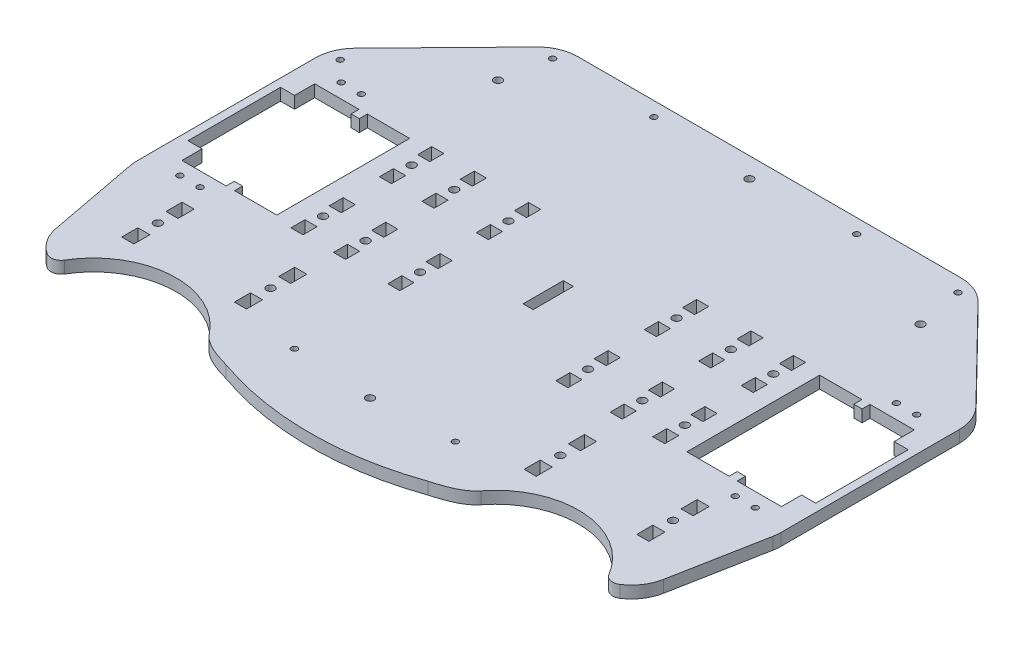
SolidWorks part; units mm, degrees
material "Balsa"
ref_plane "Plan de face" through (0, 0, 0) normal (0, 0, 1) x (1, 0, 0)
ref_plane "Plan de dessus" through (0, 0, 0) normal (0, 1, 0) x (1, 0, 0)
ref_plane "Plan de droite" through (0, 0, 0) normal (1, 0, 0) x (0, 0, -1)
sketch "Esquisse1" plane through (0, 0, 0) normal (0, 1, 0) x (1, 0, 0)
  line L0 (-159.6514, 61.9965) -> (-151.003, 16.2822)
  line L1 (131.3515, 0) -> (50.1768, 0)
  line L2 (0, 0) -> (0, 220) construction
  line L3 (95.3188, 220) -> (-95.3188, 220)
  line L4 (-160, 65.7142) -> (-160, 154.2858)
  line L5 (-154.3028, 168.2654) -> (-109.6216, 213.9796)
  line L6 (0, 110) -> (-160, 110) construction
  line L7 (154.3028, 168.2654) -> (109.6216, 213.9796)
  line L8 (160, 65.7142) -> (160, 154.2858)
  line L9 (159.6514, 61.9965) -> (151.003, 16.2822)
  line L10 (-50.1768, 0) -> (-131.3515, 0)
  arc A0 (-151.003, 16.2822) -> (-131.3515, 0) centre (-131.3515, 20) ccw
  arc A1 (-159.6514, 61.9965) -> (-160, 65.7142) centre (-140, 65.7142) cw
  arc A2 (-109.6216, 213.9796) -> (-95.3188, 220) centre (-95.3188, 200) cw
  arc A3 (-154.3028, 168.2654) -> (-160, 154.2858) centre (-140, 154.2858) ccw
  arc A4 (154.3028, 168.2654) -> (160, 154.2858) centre (140, 154.2858) cw
  arc A5 (109.6216, 213.9796) -> (95.3188, 220) centre (95.3188, 200) ccw
  arc A6 (159.6514, 61.9965) -> (160, 65.7142) centre (140, 65.7142) ccw
  arc A7 (151.003, 16.2822) -> (131.3515, 0) centre (131.3515, 20) cw
  arc A8 (-50.1768, 0) -> (50.1768, 0) centre (0, 142.6245) ccw
  dimension "D3" = 20
  dimension "D1" = 220
  dimension "D2" = 160
extrude "Boss.-Extru.1" add sketch "Esquisse1" along normal blind 6
sketch "Esquisse2" plane through (0, 6, 0) normal (0, 1, 0) x (1, 0, 0)
  line L0 (0, 220) -> (0, 0) construction
  line L1 (95.3188, 220) -> (-95.3188, 220) construction
  line L2 (0, -16) -> (-100, -16) construction
  line L3 (0, -16) -> (0, 0) construction
  line L4 (50.1768, 0) -> (131.3515, 0) construction
  line L5 (-50.1768, 0) -> (-59.2136, -20.1799)
  line L6 (50.1768, 0) -> (59.2136, -20.1799)
  arc A0 (-67.535, 9.0405) -> (-59.2136, -20.1799) centre (-100, -16) ccw
  arc A1 (-50.1768, 0) -> (50.1768, 0) centre (0, 142.6245) ccw construction
  arc A2 (67.535, 9.0405) -> (59.2136, -20.1799) centre (100, -16) cw
  spline S0 degree 3 poles (-50.1768, 0) (-51.8745, 0.5973) (-62.853, 2.9703) (-67.535, 9.0405) knots 0 0 0 0 1 1 1 1
  spline S1 degree 3 poles (50.1768, 0) (51.8745, 0.5973) (62.853, 2.9703) (67.535, 9.0405) knots 0 0 0 0 1 1 1 1
  dimension "D2" = 82
  dimension "D1" = 16
extrude "Enlèv. mat.-Extru.1" cut sketch "Esquisse2" against normal blind 6
fillet "Congé1" radius 5 2 edges at (-137.3461, 3, -0.9195) (137.3461, 3, -0.9195)
sketch "Esquisse3" plane through (0, 6, 0) normal (0, 1, 0) x (-1, 0, 0)
  line L0 (160, -110) -> (0, -110) construction
  line L1 (160, -154.2858) -> (160, -65.7142) construction
  line L2 (0, -110) -> (0, 8.569) construction
  line L3 (89.9, -119) -> (89.9, -101) construction
  line L4 (92.9, -145) -> (86.9, -145)
  line L5 (92.9, -145) -> (92.9, -138)
  line L6 (92.9, -138) -> (86.9, -138)
  line L7 (86.9, -145) -> (86.9, -138)
  line L8 (92.9, -126) -> (86.9, -126)
  line L9 (92.9, -126) -> (92.9, -119)
  line L10 (92.9, -119) -> (86.9, -119)
  line L11 (86.9, -126) -> (86.9, -119)
  line L12 (92.9, -101) -> (86.9, -101)
  line L13 (92.9, -101) -> (92.9, -94)
  line L14 (92.9, -94) -> (86.9, -94)
  line L15 (86.9, -101) -> (86.9, -94)
  line L16 (92.9, -82) -> (86.9, -82)
  line L17 (92.9, -82) -> (92.9, -75)
  line L18 (92.9, -75) -> (86.9, -75)
  line L19 (86.9, -82) -> (86.9, -75)
  line L20 (71.76, -145) -> (65.76, -145)
  line L21 (2.5, -120) -> (-2.5, -120)
  line L22 (2.5, -120) -> (2.5, -100)
  line L23 (2.5, -100) -> (-2.5, -100)
  line L24 (-2.5, -120) -> (-2.5, -100)
  line L25 (71.76, -145) -> (71.76, -138)
  line L26 (71.76, -138) -> (65.76, -138)
  line L27 (65.76, -145) -> (65.76, -138)
  line L28 (71.76, -126) -> (65.76, -126)
  line L29 (71.76, -126) -> (71.76, -119)
  line L30 (71.76, -119) -> (65.76, -119)
  line L31 (65.76, -126) -> (65.76, -119)
  line L32 (71.76, -101) -> (65.76, -101)
  line L33 (71.76, -101) -> (71.76, -94)
  line L34 (71.76, -94) -> (65.76, -94)
  line L35 (65.76, -101) -> (65.76, -94)
  line L36 (71.76, -82) -> (65.76, -82)
  line L37 (71.76, -82) -> (71.76, -75)
  line L38 (71.76, -75) -> (65.76, -75)
  line L39 (65.76, -82) -> (65.76, -75)
  line L40 (68.76, -119) -> (68.76, -101) construction
  line L41 (44.76, -145) -> (38.76, -145)
  line L42 (44.76, -145) -> (44.76, -138)
  line L43 (44.76, -138) -> (38.76, -138)
  line L44 (38.76, -145) -> (38.76, -138)
  line L45 (44.76, -126) -> (38.76, -126)
  line L46 (44.76, -126) -> (44.76, -119)
  line L47 (44.76, -119) -> (38.76, -119)
  line L48 (38.76, -126) -> (38.76, -119)
  line L49 (44.76, -101) -> (38.76, -101)
  line L50 (44.76, -101) -> (44.76, -94)
  line L51 (44.76, -94) -> (38.76, -94)
  line L52 (38.76, -101) -> (38.76, -94)
  line L53 (44.76, -82) -> (38.76, -82)
  line L54 (44.76, -82) -> (44.76, -75)
  line L55 (44.76, -75) -> (38.76, -75)
  line L56 (38.76, -82) -> (38.76, -75)
  line L57 (41.76, -119) -> (41.76, -101) construction
  line L58 (89.9, -138) -> (89.9, -126) construction
  line L59 (89.9, -94) -> (89.9, -82) construction
  line L60 (-38.76, -82) -> (-38.76, -75)
  line L61 (-44.76, -75) -> (-38.76, -75)
  line L62 (-44.76, -82) -> (-44.76, -75)
  line L63 (-44.76, -82) -> (-38.76, -82)
  line L64 (-38.76, -101) -> (-38.76, -94)
  line L65 (-44.76, -94) -> (-38.76, -94)
  line L66 (-44.76, -101) -> (-44.76, -94)
  line L67 (-44.76, -101) -> (-38.76, -101)
  line L68 (-65.76, -82) -> (-65.76, -75)
  line L69 (-71.76, -75) -> (-65.76, -75)
  line L70 (-71.76, -82) -> (-71.76, -75)
  line L71 (-71.76, -82) -> (-65.76, -82)
  line L72 (-65.76, -101) -> (-65.76, -94)
  line L73 (-71.76, -94) -> (-65.76, -94)
  line L74 (-71.76, -101) -> (-71.76, -94)
  line L75 (-71.76, -101) -> (-65.76, -101)
  line L76 (-86.9, -82) -> (-86.9, -75)
  line L77 (-92.9, -75) -> (-86.9, -75)
  line L78 (-92.9, -82) -> (-92.9, -75)
  line L79 (-92.9, -82) -> (-86.9, -82)
  line L80 (-86.9, -101) -> (-86.9, -94)
  line L81 (-92.9, -94) -> (-86.9, -94)
  line L82 (-92.9, -101) -> (-92.9, -94)
  line L83 (-92.9, -101) -> (-86.9, -101)
  line L84 (-38.76, -126) -> (-38.76, -119)
  line L85 (-44.76, -119) -> (-38.76, -119)
  line L86 (-44.76, -126) -> (-44.76, -119)
  line L87 (-44.76, -126) -> (-38.76, -126)
  line L88 (-65.76, -126) -> (-65.76, -119)
  line L89 (-71.76, -119) -> (-65.76, -119)
  line L90 (-71.76, -126) -> (-71.76, -119)
  line L91 (-71.76, -126) -> (-65.76, -126)
  line L92 (-86.9, -126) -> (-86.9, -119)
  line L93 (-92.9, -119) -> (-86.9, -119)
  line L94 (-92.9, -126) -> (-92.9, -119)
  line L95 (-92.9, -126) -> (-86.9, -126)
  line L96 (-38.76, -145) -> (-38.76, -138)
  line L97 (-44.76, -138) -> (-38.76, -138)
  line L98 (-44.76, -145) -> (-44.76, -138)
  line L99 (-44.76, -145) -> (-38.76, -145)
  line L100 (-65.76, -145) -> (-65.76, -138)
  line L101 (-71.76, -138) -> (-65.76, -138)
  line L102 (-71.76, -145) -> (-71.76, -138)
  line L103 (-71.76, -145) -> (-65.76, -145)
  line L104 (-86.9, -145) -> (-86.9, -138)
  line L105 (-92.9, -138) -> (-86.9, -138)
  line L106 (-92.9, -145) -> (-92.9, -138)
  line L107 (-92.9, -145) -> (-86.9, -145)
  line L108 (0, -110) -> (-139.191, -110) construction
  line L109 (101.9, -143) -> (122.9, -143)
  line L110 (101.9, -143) -> (101.9, -77)
  line L111 (101.9, -77) -> (122.9, -77)
  line L112 (122.9, -143) -> (122.9, -77)
  line L114 (-101.9, -143) -> (-122.9, -143)
  line L115 (-101.9, -143) -> (-101.9, -77)
  line L116 (-101.9, -77) -> (-122.9, -77)
  line L117 (-122.9, -143) -> (-122.9, -77)
  arc A0 (50.1768, 0) -> (-50.1768, 0) centre (0, -142.6245) ccw construction
  circle A1 centre (89.9, -132) radius 2
  circle A2 centre (89.9, -88) radius 2
  circle A3 centre (68.76, -88) radius 2
  circle A4 centre (68.76, -132) radius 2
  circle A5 centre (41.76, -132) radius 2
  circle A6 centre (41.76, -88) radius 2
  circle A7 centre (-41.76, -88) radius 2
  circle A8 centre (-68.76, -88) radius 2
  circle A9 centre (-89.9, -88) radius 2
  circle A10 centre (-41.76, -132) radius 2
  circle A11 centre (-68.76, -132) radius 2
  circle A12 centre (-89.9, -132) radius 2
  point P26 (89.9, -110)
  point P51 (68.76, -110)
  point P69 (41.76, -110)
  point P149 (122.9, -110)
  point P155 (-101.9, -110)
  dimension "D16" = 4
  dimension "D17" = 4
  dimension "D1" = 70
  dimension "D2" = 12
  dimension "D3" = 7
  dimension "D4" = 7
  dimension "D5" = 12
  dimension "D6" = 7
  dimension "D7" = 7
  dimension "D8" = 86.9
  dimension "D9" = 6
  dimension "D10" = 2.5
  dimension "D11" = 2.5
  dimension "D12" = 20
  dimension "D13" = 10
  dimension "D20" = 9
  dimension "D21" = 21
  dimension "D22" = 66
  dimension "D23" = 66
  dimension "D24" = 9
  dimension "D25" = 21
  dimension "D14" = 2
  dimension "D15" = 2
  dimension "D18" = 2
  dimension "D19" = 2
extrude "Enlèv. mat.-Extru.2" cut sketch "Esquisse3" against normal blind 6
sketch "Esquisse4" plane through (0, 6, 0) normal (0, 1, 0) x (1, 0, 0)
  line L0 (-160, 154.2858) -> (-160, 65.7142) construction
  line L1 (-131, 59) -> (-125, 59)
  line L2 (-131, 59) -> (-131, 51)
  line L3 (-131, 51) -> (-125, 51)
  line L4 (-125, 59) -> (-125, 51)
  line L5 (-122.9, 77) -> (-101.9, 77) construction
  line L6 (-100, 25) -> (-100, 54.6944) construction
  line L7 (-131, 37) -> (-125, 37)
  line L8 (-131, 37) -> (-131, 29)
  line L9 (-131, 29) -> (-125, 29)
  line L10 (-125, 37) -> (-125, 29)
  line L11 (-75, 37) -> (-75, 29)
  line L12 (-69, 29) -> (-75, 29)
  line L13 (-69, 37) -> (-69, 29)
  line L14 (-69, 37) -> (-75, 37)
  line L15 (-75, 59) -> (-75, 51)
  line L16 (-69, 51) -> (-75, 51)
  line L17 (-69, 59) -> (-69, 51)
  line L18 (-69, 59) -> (-75, 59)
  line L19 (0, -8.569) -> (0, 51) construction
  line L20 (69, 59) -> (75, 59)
  line L21 (69, 59) -> (69, 51)
  line L22 (69, 51) -> (75, 51)
  line L23 (75, 59) -> (75, 51)
  line L24 (69, 37) -> (75, 37)
  line L25 (69, 37) -> (69, 29)
  line L26 (69, 29) -> (75, 29)
  line L27 (75, 37) -> (75, 29)
  line L28 (125, 37) -> (125, 29)
  line L29 (131, 29) -> (125, 29)
  line L30 (131, 37) -> (131, 29)
  line L31 (131, 37) -> (125, 37)
  line L32 (125, 59) -> (125, 51)
  line L33 (131, 51) -> (125, 51)
  line L34 (131, 59) -> (131, 51)
  line L35 (131, 59) -> (125, 59)
  arc A0 (-67.535, 9.0405) -> (-135.2708, 4.9039) centre (-100, -16) ccw construction
  arc A1 (-50.1768, 0) -> (50.1768, 0) centre (0, 142.6245) ccw construction
  dimension "D1" = 29
  dimension "D2" = 6
  dimension "D3" = 8
  dimension "D4" = 18
  dimension "D5" = 30
  dimension "D6" = 8
extrude "Enlèv. mat.-Extru.3" cut sketch "Esquisse4" against normal blind 10
sketch "Esquisse5" plane through (0, 6, 0) normal (0, 1, 0) x (1, 0, 0)
  line L0 (-133.0593, 190) -> (133.0593, 190) construction
  line L1 (-109.6216, 213.9796) -> (-154.3028, 168.2654) construction
  line L2 (154.3028, 168.2654) -> (109.6216, 213.9796) construction
  line L3 (95.3188, 220) -> (-95.3188, 220) construction
  line L4 (0, 220) -> (0, 190) construction
  circle A0 centre (-105, 190) radius 2
  circle A1 centre (105, 190) radius 2
  dimension "D2" = 4
  dimension "D1" = 30
  dimension "D3" = 105
extrude "Enlèv. mat.-Extru.4" cut sketch "Esquisse5" against normal blind 10
sketch "Esquisse6" plane through (0, 6, 0) normal (0, 1, 0) x (1, 0, 0)
  line L0 (0, 220) -> (0, 164.9198) construction
  line L1 (95.3188, 220) -> (-95.3188, 220) construction
  circle A0 centre (0, 210) radius 2
  dimension "D1" = 4
  dimension "D2" = 10
extrude "Enlèv. mat.-Extru.5" cut sketch "Esquisse6" against normal blind 10
sketch "Esquisse7" plane through (0, 6, 0) normal (0, 1, 0) x (-1, 0, 0)
  line L0 (0, 8.569) -> (0, -35.6546) construction
  arc A0 (50.1768, 0) -> (-50.1768, 0) centre (0, -142.6245) ccw construction
  circle A1 centre (0, -21.431) radius 2
  dimension "D2" = 4
  dimension "D1" = 30
extrude "Enlèv. mat.-Extru.6" cut sketch "Esquisse7" against normal blind 10
sketch "Esquisse9" plane through (0, 6, 0) normal (0, 1, 0) x (-1, 0, 0)
  line L0 (128, -51) -> (128, -37) construction
  line L1 (131, -51) -> (125, -51) construction
  line L2 (125, -37) -> (131, -37) construction
  line L3 (72, -51) -> (72, -37) construction
  line L4 (75, -51) -> (69, -51) construction
  line L5 (69, -37) -> (75, -37) construction
  line L6 (-72, -51) -> (-72, -37) construction
  line L7 (-69, -51) -> (-75, -51) construction
  line L8 (-75, -37) -> (-69, -37) construction
  line L9 (-128, -51) -> (-128, -37) construction
  line L10 (-125, -51) -> (-131, -51) construction
  line L11 (-131, -37) -> (-125, -37) construction
  circle A0 centre (128, -44) radius 2
  circle A1 centre (72, -44) radius 2
  circle A2 centre (-72, -44) radius 2
  circle A3 centre (-128, -44) radius 2
  dimension "D1" = 4
  dimension "D2" = 4
  dimension "D3" = 4
  dimension "D4" = 4
extrude "Enlèv. mat.-Extru.8" cut sketch "Esquisse9" against normal blind 10
sketch "Esquisse8" plane through (0, 6, 0) normal (0, 1, 0) x (1, 0, 0)
  line L0 (122.9, 77) -> (122.9, 143) construction
  line L1 (-127, 142.9255) -> (-149, 142.9255)
  line L2 (-127, 142.9255) -> (-127, 139)
  line L3 (-127, 76.9255) -> (-149, 76.9255)
  line L4 (-156, 132.9255) -> (-156, 86.9255)
  line L5 (0, 220) -> (0, -8.569) construction
  line L6 (95.3188, 220) -> (-95.3188, 220) construction
  line L7 (-122.9, 110) -> (-101.9, 110) construction
  line L8 (-101.9, 77) -> (-101.9, 143) construction
  line L9 (-160, 154.2858) -> (-160, 65.7142) construction
  line L10 (127, 81) -> (127, 76.9255)
  line L11 (122.9, 139) -> (122.9, 81)
  line L12 (127, 81) -> (122.9, 81)
  line L13 (127, 139) -> (122.9, 139)
  line L14 (-158.521, 161.8337) -> (-140, 154.2858) construction
  line L15 (-103.0779, 218.4336) -> (-95.3188, 200) construction
  line L16 (-100.7502, 212.9035) -> (0, 212.9035) construction
  line L17 (149, 76.9255) -> (149, 86.9255)
  line L18 (156, 86.9255) -> (149, 86.9255)
  line L19 (149, 142.9255) -> (149, 132.9255)
  line L20 (-156, 132.9255) -> (-149, 132.9255)
  line L21 (-149, 142.9255) -> (-149, 132.9255)
  line L22 (156, 132.9255) -> (149, 132.9255)
  line L23 (-122.9, 143) -> (-122.9, 77) construction
  line L24 (-156, 86.9255) -> (-149, 86.9255)
  line L25 (-149, 76.9255) -> (-149, 86.9255)
  line L26 (-127, 139) -> (-122.9, 139)
  line L27 (-101.9, 143) -> (-122.9, 143) construction
  line L28 (-127, 81) -> (-122.9, 81)
  line L29 (-122.9, 139) -> (-122.9, 81)
  line L30 (-127, 81) -> (-127, 76.9255)
  line L31 (-122.9, 77) -> (-101.9, 77) construction
  line L32 (156, 132.9255) -> (156, 86.9255)
  line L33 (127, 76.9255) -> (149, 76.9255)
  line L34 (127, 142.9255) -> (127, 139)
  line L35 (127, 142.9255) -> (149, 142.9255)
  line L36 (-138, 76.9255) -> (-138, 69.9255) construction
  line L37 (-143, 76.9255) -> (-133, 76.9255) construction
  line L38 (-143, 76.9255) -> (-143, 69.9255) construction
  line L39 (-143, 69.9255) -> (-133, 69.9255) construction
  line L40 (-133, 76.9255) -> (-133, 69.9255) construction
  arc A0 (-154.3028, 168.2654) -> (-160, 154.2858) centre (-140, 154.2858) ccw construction
  arc A1 (-95.3188, 220) -> (-109.6216, 213.9796) centre (-95.3188, 200) ccw construction
  circle A2 centre (-152.9647, 159.5693) radius 1.5
  circle A3 centre (-100.7502, 212.9035) radius 1.5
  circle A4 centre (-50.3751, 212.9035) radius 1.5
  circle A5 centre (50.3751, 212.9035) radius 1.5
  circle A6 centre (100.7502, 212.9035) radius 1.5
  circle A7 centre (-143, 69.9255) radius 1.5
  arc A8 (-50.1768, 0) -> (50.1768, 0) centre (0, 142.6245) ccw construction
  circle A9 centre (-40, 23.831) radius 1.5
  circle A10 centre (40, 23.831) radius 1.5
  circle A11 centre (-133, 69.9255) radius 1.5
  circle A12 centre (-133, 150.0745) radius 1.5
  circle A13 centre (-143, 150.0745) radius 1.5
  circle A14 centre (133, 69.9255) radius 1.5
  circle A15 centre (143, 69.9255) radius 1.5
  circle A16 centre (143, 150.0745) radius 1.5
  circle A17 centre (133, 150.0745) radius 1.5
  dimension "D3" = 3
  dimension "D4" = 3
  dimension "D7" = 3
  dimension "D8" = 3
  dimension "D19" = 3
  dimension "D20" = 3
  dimension "D1" = 66
  dimension "D2" = 4
  dimension "D5" = 14
  dimension "D6" = 14
  dimension "D9" = 40
  dimension "D10" = 32.4
  dimension "D11" = 7
  dimension "D12" = 10
  dimension "D13" = 10
  dimension "D14" = 4
  dimension "D15" = 4
  dimension "D16" = 22
  dimension "D17" = 7
  dimension "D18" = 10
extrude "Enlèv. mat.-Extru.7" cut sketch "Esquisse8" against normal blind 10
